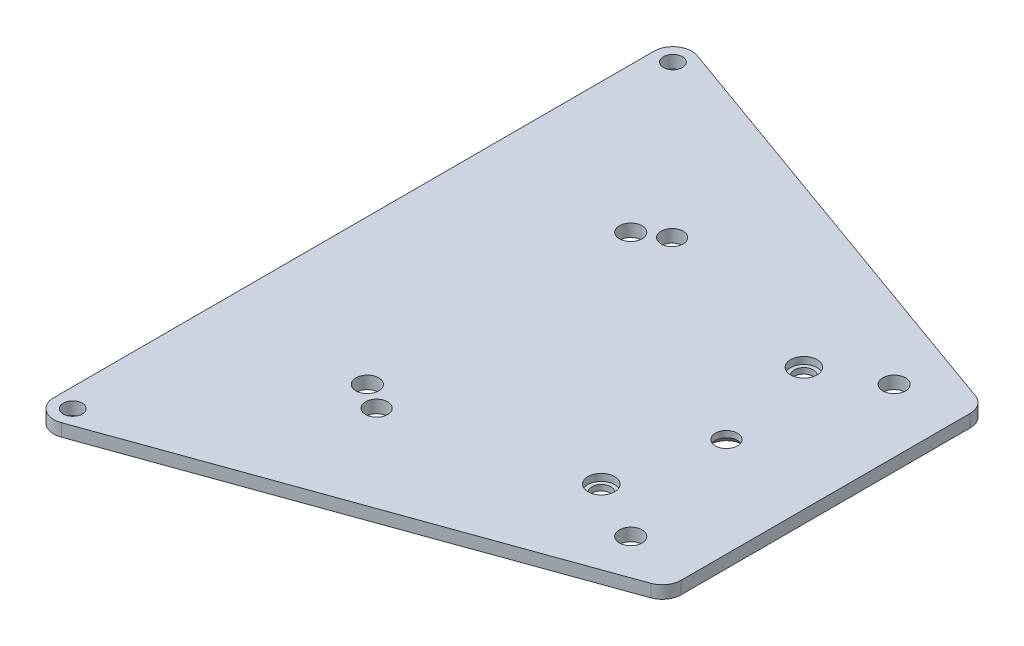
SolidWorks part; units mm, degrees
ref_plane "Front Plane" through (0, 0, 0) normal (0, 0, 1) x (1, 0, 0)
ref_plane "Top Plane" through (0, 0, 0) normal (0, 1, 0) x (1, 0, 0)
ref_plane "Right Plane" through (0, 0, 0) normal (1, 0, 0) x (0, 0, -1)
sketch "Croquis1" plane through (0, 0, 0) normal (0, 1, 0) x (1, 0, 0)
  line L0 (0, 0) -> (0, -95.05) construction
  line L1 (1.0124, 2.824) -> (69.7324, -21.8124)
  line L2 (71.72, -24.6364) -> (71.72, -70.4136)
  line L3 (69.7324, -73.2376) -> (1.0124, -97.874)
  line L4 (-3, -95.05) -> (-3, 0)
  circle A0 centre (20, -26.675) radius 1.8
  circle A1 centre (20, -68.395) radius 1.8
  circle A2 centre (61.72, -26.675) radius 1.8
  circle A3 centre (61.72, -68.395) radius 1.8
  circle A4 centre (0, 0) radius 1.5
  circle A5 centre (0, -95.05) radius 1.5
  circle A6 centre (52.22, -31.49) radius 1.5
  circle A7 centre (52.22, -63.56) radius 1.5
  arc A8 (1.0124, -97.874) -> (-3, -95.05) centre (0, -95.05) cw
  arc A9 (-3, 0) -> (1.0124, 2.824) centre (0, 0) cw
  arc A10 (71.72, -70.4136) -> (69.7324, -73.2376) centre (68.72, -70.4136) cw
  arc A11 (69.7324, -21.8124) -> (71.72, -24.6364) centre (68.72, -24.6364) cw
  circle A12 centre (24, -70.925) radius 1.75
  circle A13 centre (24, -24.125) radius 1.75
  circle A14 centre (56, -47.525) radius 1.75
  point P17 (0, -47.525)
  point P24 (71.72, -47.525)
  point P33 (-3, -47.525)
  point P36 (71.72, -72.525)
  point P39 (71.72, -22.525)
  dimension "D3" = 3.6
  dimension "D4" = 3
  dimension "D11" = 3
  dimension "D14" = 3
  dimension "D16" = 3.5
  dimension "D1" = 41.72
  dimension "D2" = 41.72
  dimension "D5" = 95.05
  dimension "D6" = 52.22
  dimension "D7" = 32.07
  dimension "D8" = 16.035
  dimension "D9" = 20.85
  dimension "D10" = 20
  dimension "D12" = 50
  dimension "D13" = 10
  dimension "D15" = 46.8
  dimension "D17" = 23.4
  dimension "D18" = 32
  dimension "D19" = 24
extrude "Saliente-Extruir1" add sketch "Croquis1" along normal blind 2
sketch "Croquis2" plane through (0, 0, 0) normal (0, -1, 0) x (1, 0, 0)
  circle A0 centre (56, 47.525) radius 2.6
  dimension "D1" = 5.2
extrude "Cortar-Extruir1" cut sketch "Croquis2" against normal blind 1 draft 40
sketch "Croquis3" plane through (0, 2, 0) normal (0, 1, 0) x (1, 0, 0)
  circle A0 centre (52.22, -31.49) radius 2.1
  circle A1 centre (52.22, -63.56) radius 2.1
  dimension "D1" = 4.2
extrude "Cortar-Extruir2" cut sketch "Croquis3" against normal blind 1.1
equation "\"D8@Croquis1\"=32.07/2"
equation "\"D17@Croquis1\"=\"D15@Croquis1\"/2"
